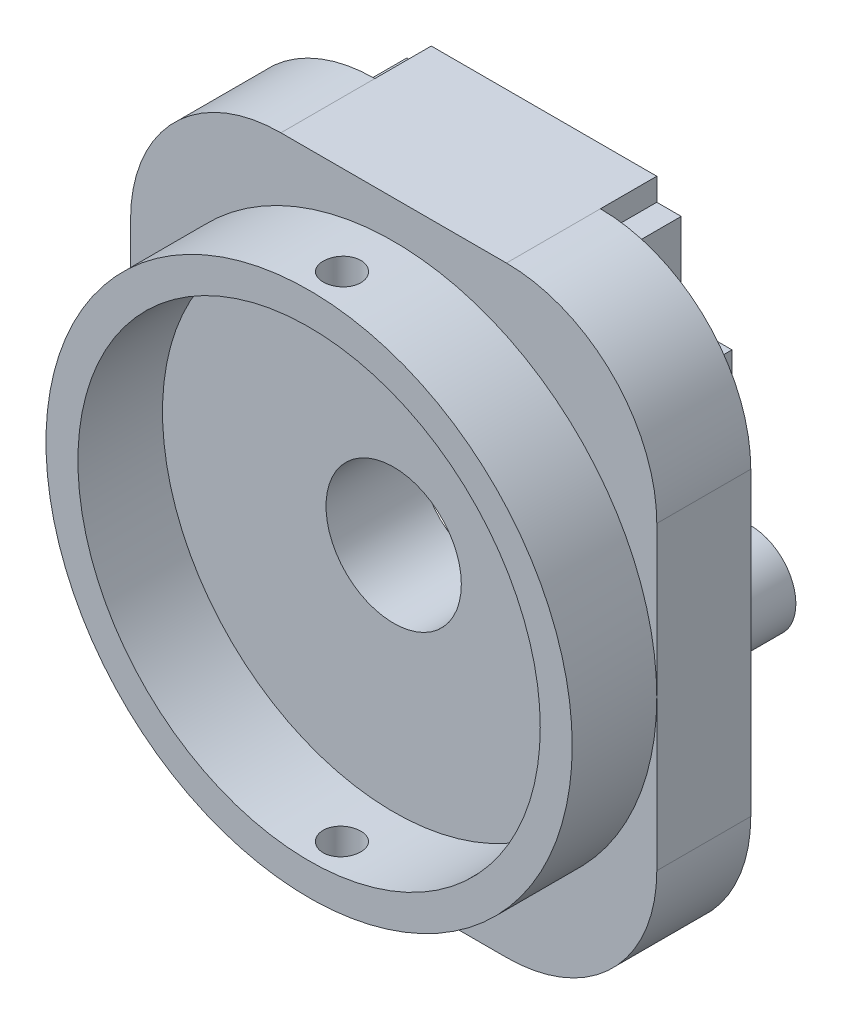
SolidWorks part; units mm, degrees
ref_plane "정면" through (0, 0, 0) normal (0, 0, 1) x (1, 0, 0)
ref_plane "윗면" through (0, 0, 0) normal (0, 1, 0) x (1, 0, 0)
ref_plane "우측면" through (0, 0, 0) normal (1, 0, 0) x (0, 0, -1)
sketch "스케치1" plane through (0, 0, 0) normal (0, 0, 1) x (1, 0, 0)
  line L1 (-6, 16) -> (6, 16)
  line L2 (-14, 8) -> (-14, -8)
  line L3 (-6, -16) -> (6, -16)
  line L4 (14, 8) -> (14, -8)
  line L6 (-14, 0) -> (14, 0) construction
  line L7 (0, 16) -> (0, -16) construction
  arc A0 (-6, -16) -> (-14, -8) centre (-6, -8) cw
  arc A1 (6, -16) -> (14, -8) centre (6, -8) ccw
  arc A2 (14, 8) -> (6, 16) centre (6, 8) ccw
  arc A3 (-6, 16) -> (-14, 8) centre (-6, 8) ccw
  dimension "D3" = 12
  dimension "D1" = 28
  dimension "D2" = 32
extrude "보스-돌출1" add sketch "스케치1" along normal blind 5 contours A3 L2 A0 L3 A1 L4 A2 L1
sketch "스케치2" plane through (0, 0, 5) normal (0, 0, 1) x (1, 0, 0)
  circle A0 centre (0, 0) radius 14
  circle A1 centre (0, 0) radius 12.3
  dimension "D1" = 28
  dimension "D2" = 24.6
extrude "보스-돌출2" add sketch "스케치2" along normal blind 4.5
sketch "스케치3" plane through (0, 0, 0) normal (0, 0, -1) x (-1, 0, 0)
  line L0 (9, 9) -> (-9, -9) construction
  line L1 (-10, 10) -> (-7.3, 10)
  line L2 (-10, 10) -> (-10, 2.4)
  line L3 (-10, -10) -> (10, -10)
  line L4 (10, 10) -> (10, 2.4)
  line L5 (-9, 9) -> (9, 9)
  line L6 (-9, 9) -> (-9, -9)
  line L7 (-9, -9) -> (9, -9)
  line L8 (9, 9) -> (9, -9)
  line L9 (-10, 10) -> (10, -10) construction
  line L10 (-10.7152, 0) -> (11.3029, 0) construction
  line L11 (0, 0) -> (0, 17.3363) construction
  line L12 (-11, 2.4) -> (-10, 2.4)
  line L13 (-11, -2.4) -> (-10, -2.4)
  line L14 (11, -2.4) -> (10, -2.4)
  line L15 (11, 2.4) -> (10, 2.4)
  line L16 (10, -2.4) -> (10, -10)
  line L17 (-10, -2.4) -> (-10, -10)
  line L18 (-6, 16) -> (6, 16)
  line L19 (6, 16) -> (-6, 16) construction
  line L20 (6, 16) -> (6, 14.8)
  line L21 (6, 14.8) -> (7.3, 14.8)
  line L22 (7.3, 14.8) -> (7.3, 10)
  line L27 (-6, 16) -> (-6, 14.8)
  line L28 (-6, 14.8) -> (-7.3, 14.8)
  line L29 (-7.3, 14.8) -> (-7.3, 10)
  line L34 (7.3, 10) -> (10, 10)
  arc A0 (11, -2.4) -> (11, 2.4) centre (11, 0) ccw
  arc A1 (-11, 2.4) -> (-11, -2.4) centre (-11, 0) ccw
  dimension "D6" = 4.8
  dimension "D1" = 20
  dimension "D2" = 20
  dimension "D3" = 18
  dimension "D4" = 18
  dimension "D5" = 22
  dimension "D7" = 12
  dimension "D8" = 1.2
  dimension "D10" = 14.6
extrude "보스-돌출3" add sketch "스케치3" along normal blind 3
sketch "스케치4" plane through (0, 0, 0) normal (0, 0, 1) x (1, 0, 0)
  circle A0 centre (0, 0) radius 3.6
  dimension "D1" = 7.2
extrude "컷-돌출2" cut sketch "스케치4" along normal through all
sketch "스케치5" plane through (0, 0, -3) normal (0, 0, -1) x (-1, 0, 0)
  point P0 (11, 0)
  point P1 (-11, 0)
hole_wizard "M2 여유 구멍1" positions "3D스케치1" profile "스케치6" hole size "M2" standard "Ansi Metric"
sketch3d "3D스케치1"
  point P0 (-11, 0, -3)
  point P3 (11, 0, -3)
sketch "스케치6" plane through (-11, 0, -3) normal (1, 0, 0) x (0, 1, 0)
  line L0 (0, 0) -> (0, 3.721)
  line L1 (0, 3.721) -> (1.2, 3)
  line L2 (1.2, 3) -> (1.2, 0)
  line L5 (1.2, 0) -> (0, 0)
  line L10 (0, 3.721) -> (-1.2, 3) construction
  line L11 (0, -6.35) -> (0, 107.95) construction
  dimension "구멍 지름" = 2.4
  dimension "구멍 깊이" = 3
  dimension "드릴 각도" = 118
sketch "Sketch1" plane through (0, 0, 0) normal (0, 1, 0) x (1, 0, 0)
  line L0 (0, 0) -> (0, -12.3957) construction
  line L1 (-14, -9.5) -> (14, -9.5) construction
  circle A0 centre (0, -7.75) radius 1
  dimension "D1" = 2
  dimension "D2" = 1.75
extrude "Cut-Extrude1" cut sketch "Sketch1" against normal through all and the other way through all
